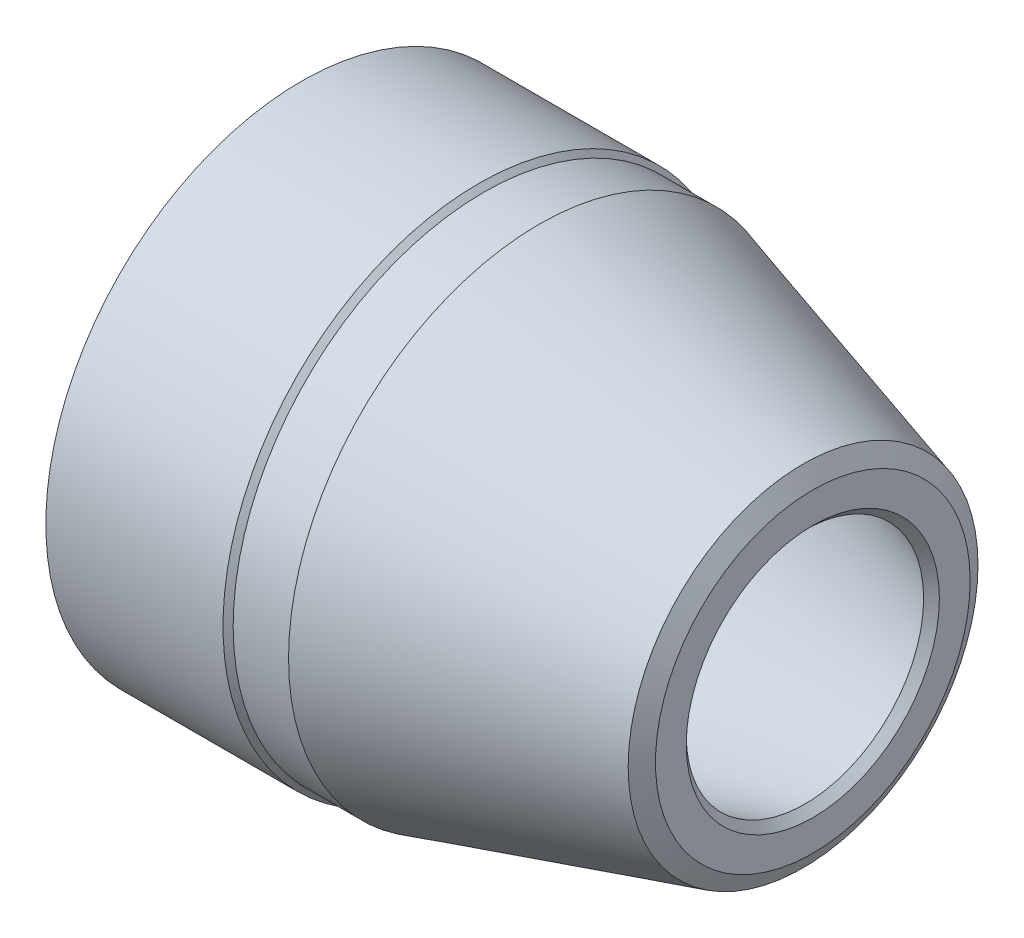
SolidWorks part; units mm, degrees
material "1.8901 (S460N)"
ref_plane "Plan de face" through (0, 0, 0) normal (0, 0, 1) x (1, 0, 0)
ref_plane "Plan de dessus" through (0, 0, 0) normal (0, 1, 0) x (1, 0, 0)
ref_plane "Plan de droite" through (0, 0, 0) normal (1, 0, 0) x (0, 0, -1)
sketch "Esquisse1" plane through (0, 0, 0) normal (0, 0, 1) x (1, 0, 0)
  line L0 (0, 0) -> (-17.2999, 0) construction
  line L1 (0, 21.5) -> (0, 25.25)
  line L2 (0, 25.25) -> (17.5, 25.25)
  line L3 (17.5, 25.25) -> (18, 24.75)
  line L4 (18, 24.75) -> (23.4725, 24.75)
  line L5 (23.4725, 24.75) -> (50.5, 17)
  line L6 (50.5, 17) -> (50.5, 11.5)
  line L7 (50.5, 11.5) -> (17.3696, 21)
  line L8 (17.3696, 21) -> (15.8696, 22.5)
  line L9 (15.8696, 22.5) -> (7, 22.5)
  line L10 (7, 22.5) -> (7, 21.5)
  line L11 (7, 21.5) -> (0, 21.5)
  dimension "D1" = 23
  dimension "D2" = 34
  dimension "D3" = 43
  dimension "D4" = 1
  dimension "D5" = 50.5
  dimension "D6" = 45
  dimension "D7" = 18
  dimension "D8" = 0.5
  dimension "D9" = 49.5
  dimension "D10" = 0.5
  dimension "D11" = 7
  dimension "D12" = 16
revolve "Révolution1" add sketch "Esquisse1" angle 360 about L0
cosmetic thread "Représentation de filetage1" parameters "D2"=45
chamfer "Chanfrein1" distance 1 angle 45 1 edges at (50.5, 0, -17)
